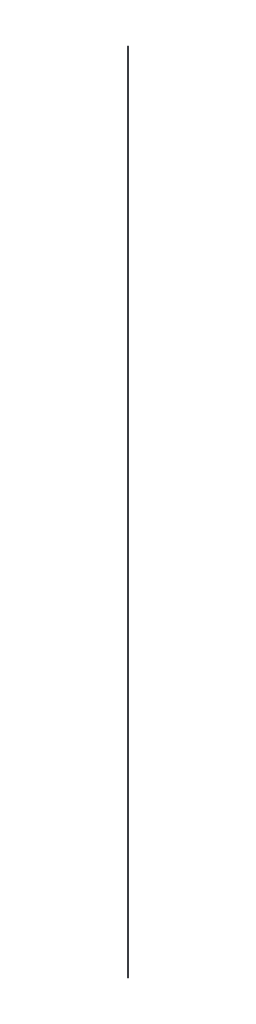
SolidWorks part; units mm, degrees
material "3.1655 (EN AW-2011)"
ref_plane "Plano frontal" through (0, 0, 0) normal (0, 0, 1) x (1, 0, 0)
ref_plane "Plano superior" through (0, 0, 0) normal (0, 1, 0) x (1, 0, 0)
ref_plane "Plano direito" through (0, 0, 0) normal (1, 0, 0) x (0, 0, -1)
sketch "Esboço2" plane through (0, 0, 0) normal (0, 1, 0) x (1, 0, 0)
  circle A0 centre (0, 0) radius 1
  dimension "D1" = 2
extrude "Ressalto-extrusão1" add sketch "Esboço2" along normal blind 3000
